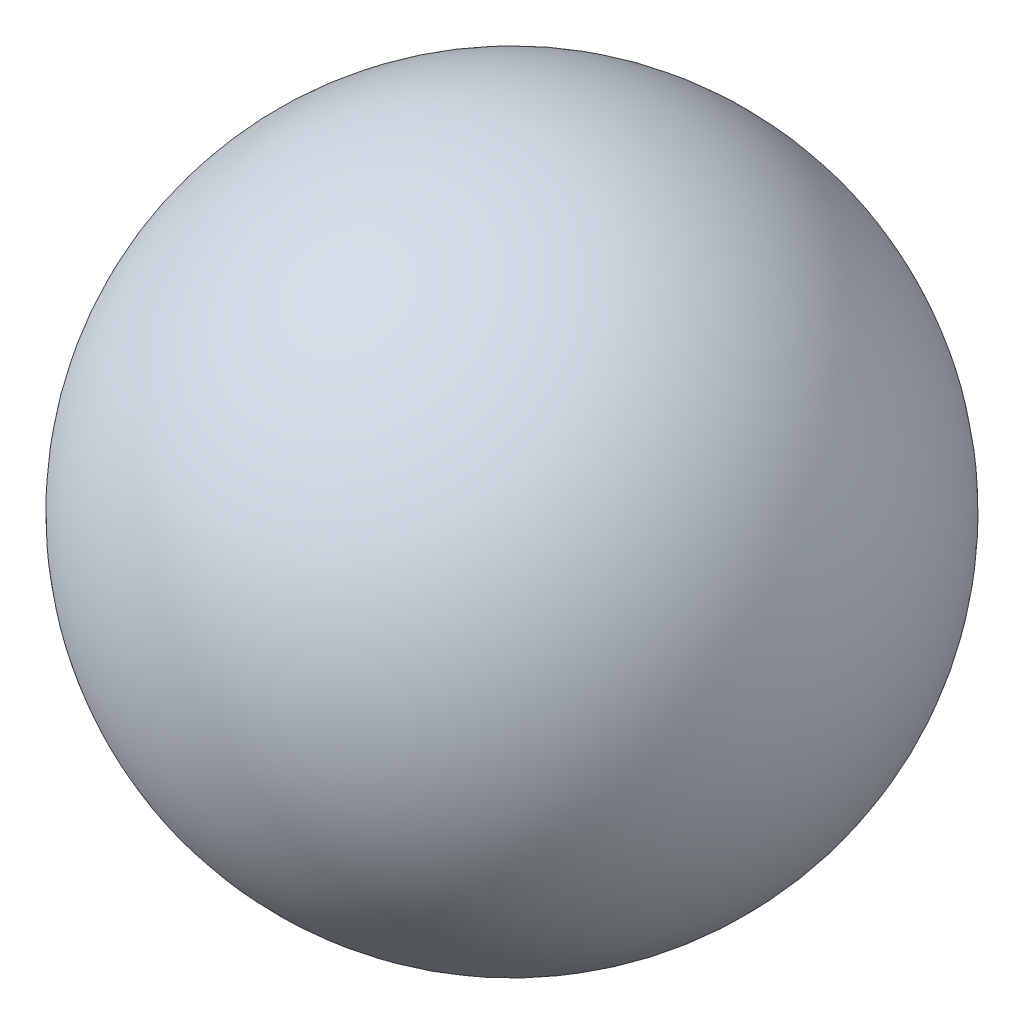
SolidWorks part; units mm, degrees
ref_plane "Front Plane" through (0, 0, 0) normal (0, 0, 1) x (1, 0, 0)
ref_plane "Top Plane" through (0, 0, 0) normal (0, 1, 0) x (1, 0, 0)
ref_plane "Right Plane" through (0, 0, 0) normal (1, 0, 0) x (0, 0, -1)
sketch "Sketch1" plane through (0, 0, 0) normal (0, 1, 0) x (1, 0, 0)
  line L0 (0, 8) -> (0, -8)
  line L1 (0, 0) -> (8, 0) construction
  arc A0 (0, -8) -> (0, 8) centre (0, 0) ccw
  dimension "D1" = 8
revolve "Revolve1" add sketch "Sketch1" angle 360 about L0
sketch "Sketch2" plane through (0, 0, 0) normal (0, 1, 0) x (1, 0, 0)
  line L0 (0, 8) -> (0, 0)
  line L1 (0, 0) -> (8, 0) construction
